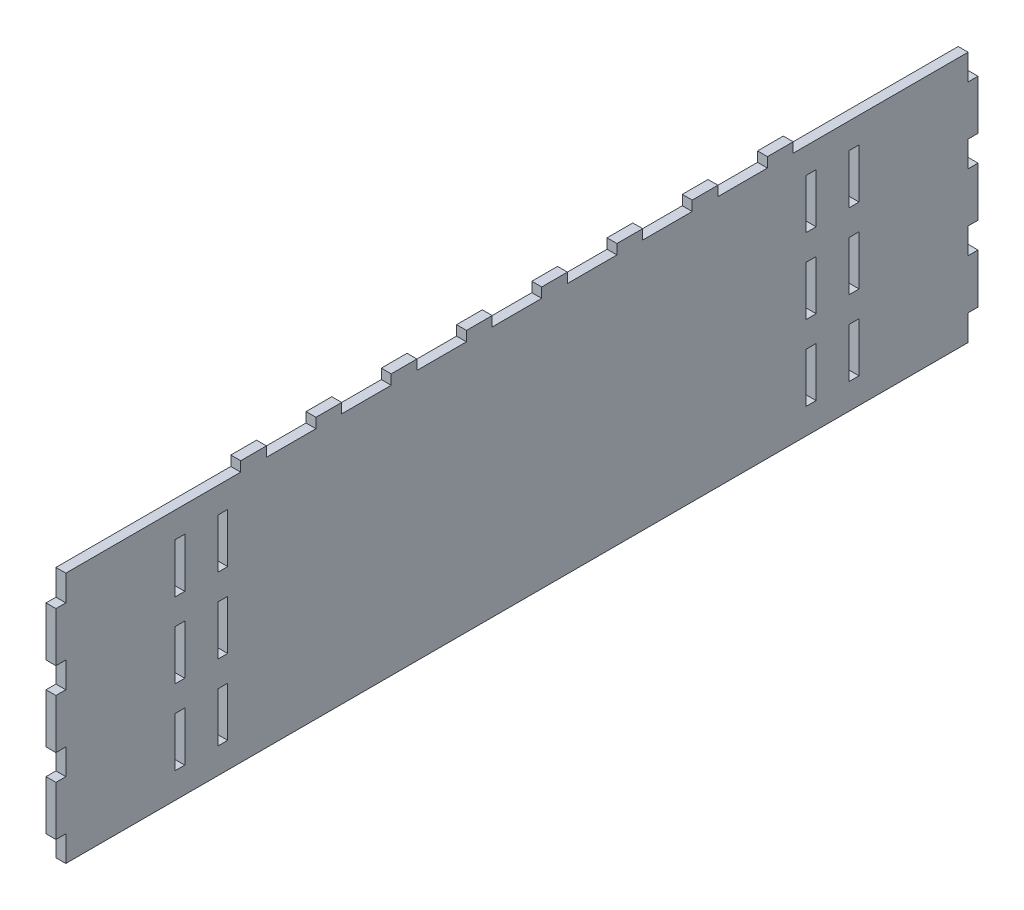
SolidWorks part; units mm, degrees
material "ENPH 253 Hardboard"
ref_plane "Front Plane" through (0, 0, 0) normal (0, 0, 1) x (1, 0, 0)
ref_plane "Top Plane" through (0, 0, 0) normal (0, 1, 0) x (1, 0, 0)
ref_plane "Right Plane" through (0, 0, 0) normal (1, 0, 0) x (0, 0, -1)
sketch "Sketch1" plane through (0, 0, 0) normal (1, 0, 0) x (0, 0, -1)
  line L1 (-139.7, 38.1) -> (139.7, 38.1)
  line L2 (-139.7, 38.1) -> (-139.7, -38.1)
  line L3 (-139.7, -38.1) -> (139.7, -38.1)
  line L4 (139.7, 38.1) -> (139.7, -38.1)
  line L5 (-139.7, 38.1) -> (139.7, -38.1) construction
  line L6 (-139.7, -38.1) -> (139.7, 38.1) construction
  point P0 (0, 0)
  dimension "D1" = 279.4
  dimension "D2" = 76.2
extrude "Boss-Extrude1" add sketch "Sketch1" against normal blind 3 contours L2 L3 L4 L1
sketch "Sketch3" plane through (-3, 0, 0) normal (-1, 0, 0) x (0, 0, 1)
  line L2 (-139.7, 38.1) -> (-139.7, -38.1) construction
  line L7 (-100.65, 30.3) -> (-103.65, 30.3)
  line L8 (-100.65, 30.3) -> (-100.65, 15.3)
  line L9 (-139.7, 38.1) -> (-136.7, 38.1)
  line L10 (-139.7, 38.1) -> (-139.7, 30.3)
  line L11 (-139.7, 30.3) -> (-136.7, 30.3)
  line L12 (-136.7, 38.1) -> (-136.7, 30.3)
  line L13 (-100.65, 15.3) -> (-103.65, 15.3)
  line L14 (-103.65, 30.3) -> (-103.65, 15.3)
  line L15 (139.7, 38.1) -> (-139.7, 38.1) construction
  dimension "D5" = 15
  dimension "D6" = 3
  dimension "D7" = 36.05
  dimension "D8" = 7.8
  dimension "D9" = 7.8
  dimension "D10" = 3
extrude "Cut-Extrude1" cut sketch "Sketch3" against normal through all
pattern_linear "LPattern1" count 4 spacing 22.8 along (0, -1, 0) of "Cut-Extrude1"
mirror "Mirror1" about plane through (0, 0, 0) normal (0, 0, 1) of "LPattern1", "Cut-Extrude1"
sketch "Sketch4" plane through (0, 0, 0) normal (1, 0, 0) x (0, 0, -1)
  line L0 (-100.65, 15.3) -> (-100.65, 30.3) construction
  line L1 (-90.65, 30.3) -> (-87.65, 30.3)
  line L2 (-90.65, 30.3) -> (-90.65, 15.3)
  line L3 (-90.65, 15.3) -> (-87.65, 15.3)
  line L4 (-87.65, 30.3) -> (-87.65, 15.3)
  line L5 (-136.7, 38.1) -> (136.7, 38.1) construction
  dimension "D1" = 10
  dimension "D2" = 3
  dimension "D3" = 7.8
  dimension "D4" = 15
extrude "Cut-Extrude2" cut sketch "Sketch4" against normal blind 10
pattern_linear "LPattern2" count 3 spacing 22.8 along (0, -1, 0) of "Cut-Extrude2"
mirror "Mirror2" about plane through (0, 0, 0) normal (0, 0, 1) of "LPattern2", "Cut-Extrude2"
sketch "Sketch5" plane through (0, 38.1, 0) normal (0, 1, 0) x (1, 0, 0)
  line L0 (-3, -136.7) -> (-3, 136.7) construction
  line L1 (-3, -75.9) -> (0, -75.9)
  line L2 (-3, -75.9) -> (-3, -83.7)
  line L3 (-3, -83.7) -> (0, -83.7)
  line L4 (0, -75.9) -> (0, -83.7)
  line L5 (0, -136.7) -> (-3, -136.7) construction
  dimension "D1" = 53
  dimension "D2" = 7.8
  dimension "D3" = 3
extrude "Boss-Extrude2" add sketch "Sketch5" along normal blind 3
pattern_linear "LPattern3" count 8 spacing 22.8 along (0, 0, -1) of "Boss-Extrude2"
